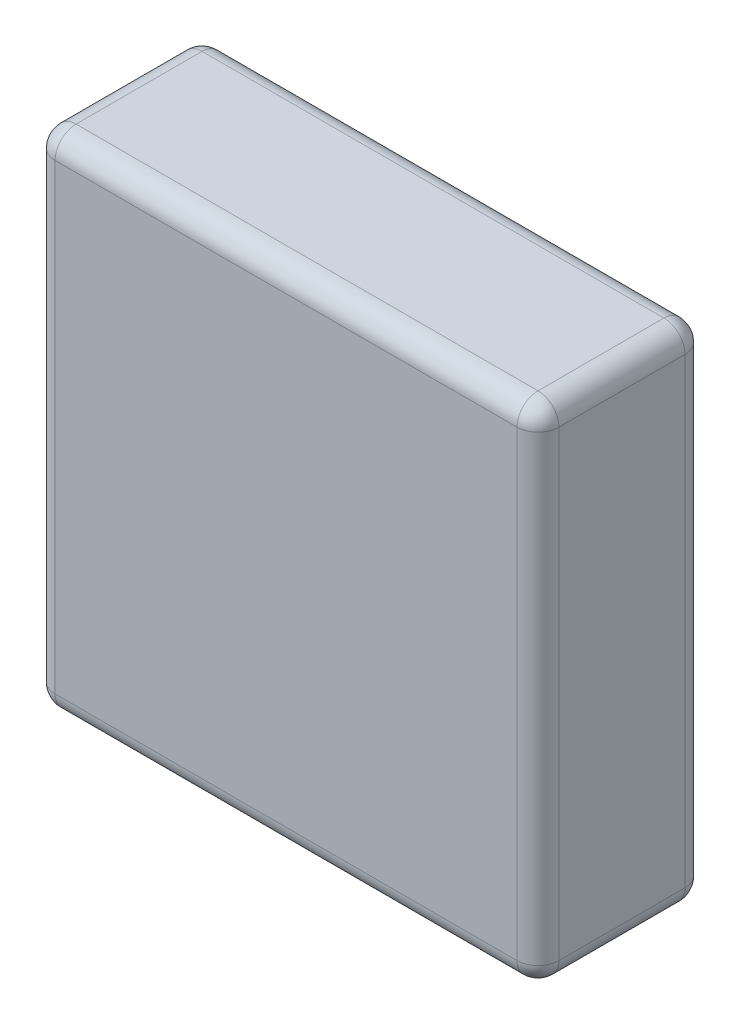
SolidWorks part; units mm, degrees
material "铍"
ref_plane "前视基准面" through (0, 0, 0) normal (0, 0, 1) x (1, 0, 0)
ref_plane "上视基准面" through (0, 0, 0) normal (0, 1, 0) x (1, 0, 0)
ref_plane "右视基准面" through (0, 0, 0) normal (1, 0, 0) x (0, 0, -1)
other "Configuration Table"
sketch "草图1" plane through (0, 0, 0) normal (0, 0, 1) x (1, 0, 0)
  line L1 (0, 0) -> (120, 0)
  line L2 (0, 0) -> (0, -120)
  line L3 (0, -120) -> (120, -120)
  line L4 (120, 0) -> (120, -120)
  dimension "D1" = 120
  dimension "D2" = 120
extrude "凸台-拉伸1" add sketch "草图1" along normal blind 40
fillet "圆角1" radius 5 12 edges at (60, -120, 0) (60, -120, 40) (60, 0, 40) (0, 0, 20) (120, -120, 20) (0, -120, 20) (120, 0, 20) (0, -60, 0) (0, -60, 40) (120, -60, 40) (120, -60, 0) (60, 0, 0)
